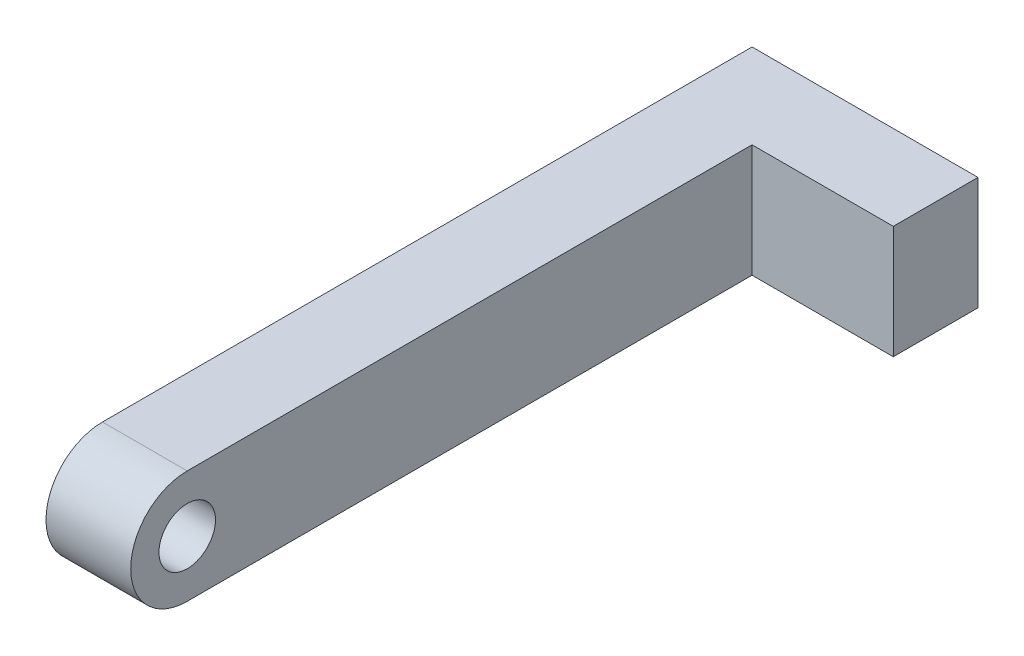
SolidWorks part; units mm, degrees
ref_plane "Płaszczyzna przednia" through (0, 0, 0) normal (0, 0, 1) x (1, 0, 0)
ref_plane "Płaszczyzna górna" through (0, 0, 0) normal (0, 1, 0) x (1, 0, 0)
ref_plane "Płaszczyzna prawa" through (0, 0, 0) normal (1, 0, 0) x (0, 0, -1)
sketch "Szkic1" plane through (0, 0, 0) normal (1, 0, 0) x (0, 0, -1)
  line L0 (0, 4) -> (46, 4)
  line L1 (0, -4) -> (46, -4)
  line L2 (46, -4) -> (46, 4)
  circle A0 centre (0, 0) radius 2
  circle A1 centre (0, 0) radius 4
extrude "Dodanie-wyciągnięcie1" add sketch "Szkic1" along normal blind 6 contours A1 L1 L2 L0 | A1 A0
sketch "Szkic2" plane through (6, 0, 0) normal (1, 0, 0) x (0, 0, -1)
  line L0 (46, 4) -> (46, -4)
  line L1 (46, -4) -> (40, -4)
  line L2 (0, -4) -> (46, -4) construction
  line L3 (40, -4) -> (40, 4)
  line L4 (0, 4) -> (46, 4) construction
  line L5 (40, 4) -> (46, 4)
extrude "Dodanie-wyciągnięcie2" add sketch "Szkic2" along normal blind 10
